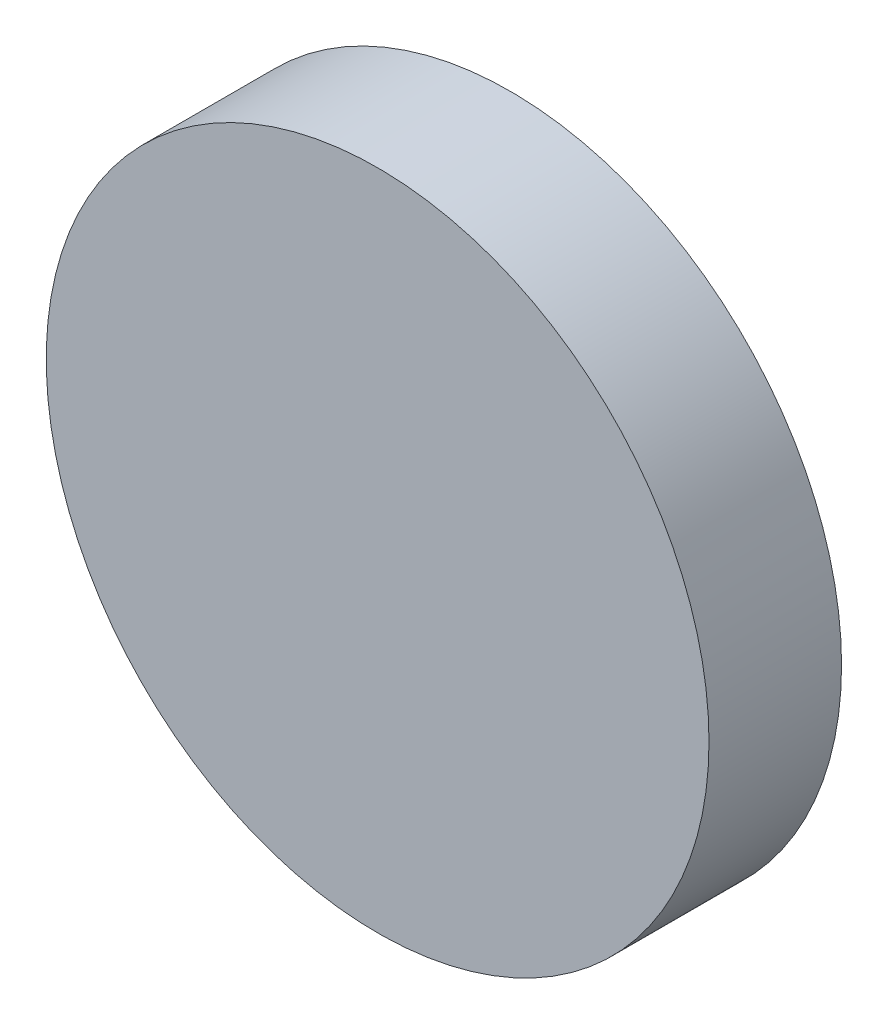
SolidWorks part; units mm, degrees
ref_plane "前视基准面" through (0, 0, 0) normal (0, 0, 1) x (1, 0, 0)
ref_plane "上视基准面" through (0, 0, 0) normal (0, 1, 0) x (1, 0, 0)
ref_plane "右视基准面" through (0, 0, 0) normal (1, 0, 0) x (0, 0, -1)
other "Configuration Table"
sketch "草图1" plane through (0, 0, 0) normal (0, 0, 1) x (1, 0, 0)
  circle A0 centre (0, 0) radius 30
extrude "凸台-拉伸1" add sketch "草图1" against normal blind 12
sketch "草图2" plane through (0, 0, 0) normal (0, 0, 1) x (1, 0, 0)
  circle A0 centre (0, 0) radius 15
sketch "草图3" plane through (0, 0, 0) normal (0, 0, 1) x (1, 0, 0)
  circle A0 centre (0, 22) radius 3
